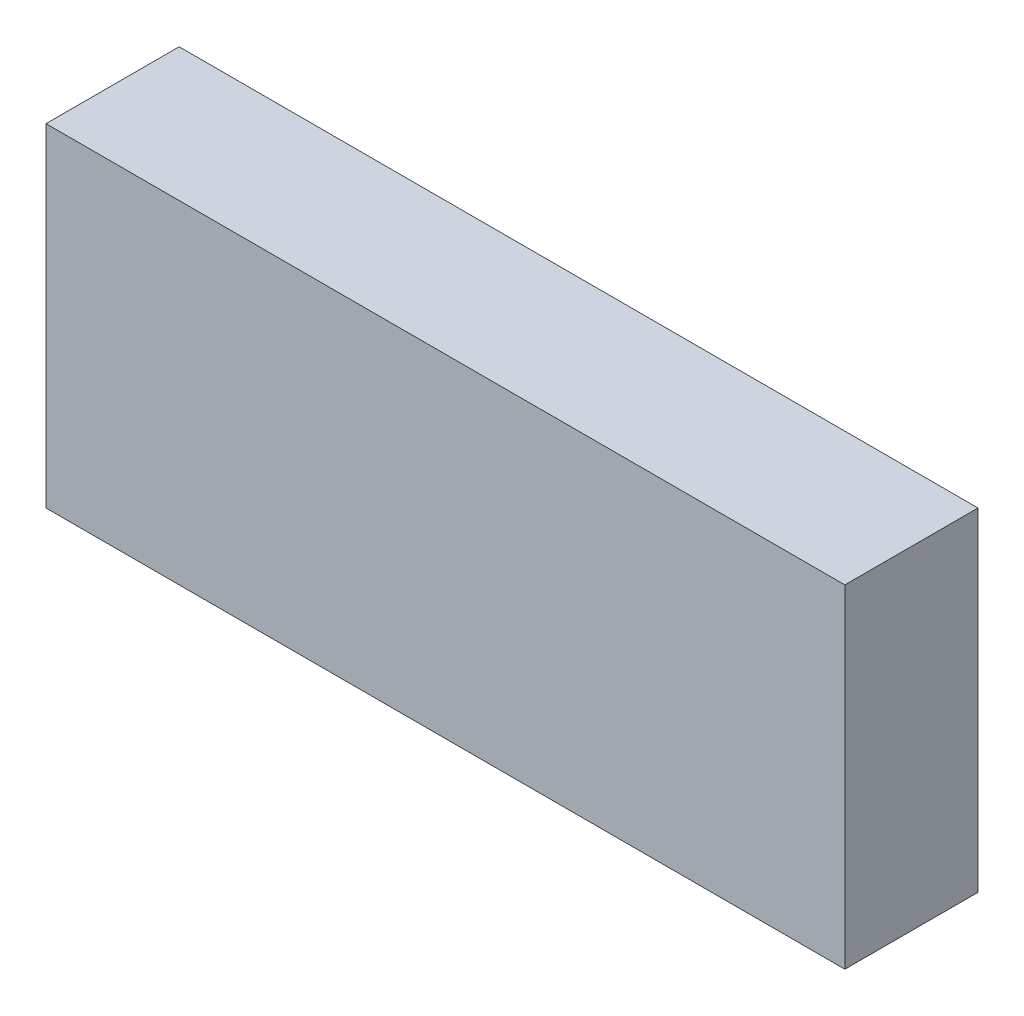
SolidWorks part; units mm, degrees
material "Nylon 101"
ref_plane "Front" through (0, 0, 0) normal (0, 0, 1) x (1, 0, 0)
ref_plane "Top" through (0, 0, 0) normal (0, 1, 0) x (1, 0, 0)
ref_plane "Right" through (0, 0, 0) normal (1, 0, 0) x (0, 0, -1)
sketch "Sketch1" plane through (0, 0, 0) normal (0, 0, 1) x (1, 0, 0)
  line L1 (-30, 0) -> (30, 0)
  line L2 (-30, 0) -> (-30, 25)
  line L3 (-30, 25) -> (30, 25)
  line L4 (30, 0) -> (30, 25)
  dimension "D1" = 60
  dimension "D2" = 25
extrude "Boss-Extrude1" add sketch "Sketch1" along normal blind 10
